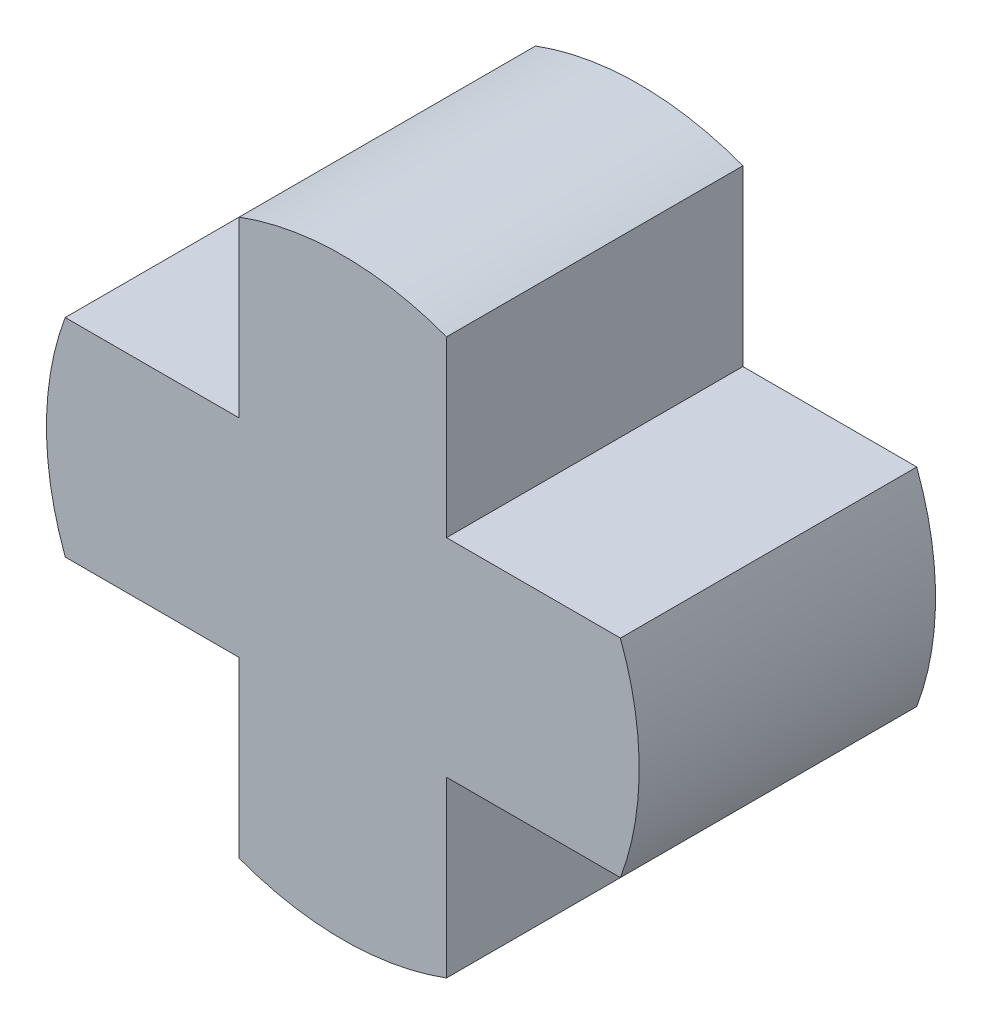
SolidWorks part; units mm, degrees
ref_plane "정면" through (0, 0, 0) normal (0, 0, 1) x (1, 0, 0)
ref_plane "윗면" through (0, 0, 0) normal (0, 1, 0) x (1, 0, 0)
ref_plane "우측면" through (0, 0, 0) normal (1, 0, 0) x (0, 0, -1)
sketch "스케치1" plane through (0, 0, 0) normal (0, 0, 1) x (1, 0, 0)
  line L1 (3.5, -10) -> (-3.5, -10)
  line L2 (3.5, -10) -> (3.5, 9.3675)
  line L4 (-3.5, -10) -> (-3.5, 9.3675)
  line L5 (3.5, -10) -> (-3.3035, 9.4386) construction
  line L6 (3.3035, 9.4386) -> (-3.5, -10) construction
  line L7 (-9.3675, -3.5) -> (9.3675, -3.5)
  line L9 (-9.3675, 3.5) -> (9.3675, 3.5)
  line L11 (-9.4386, -3.3035) -> (9.4386, 3.3035) construction
  line L12 (-9.4386, 3.3035) -> (9.4386, -3.3035) construction
  circle A0 centre (0, 0) radius 10
  dimension "D1" = 20
  dimension "D2" = 7
  dimension "D3" = 7
extrude "보스-돌출1" add sketch "스케치1" along normal blind 10 contours L2 A0 L4 L9 | L9 A0 L7 L4 | L9 L4 L7 L2 | L4 A0 L2 L7 | L7 A0 L9 L2
